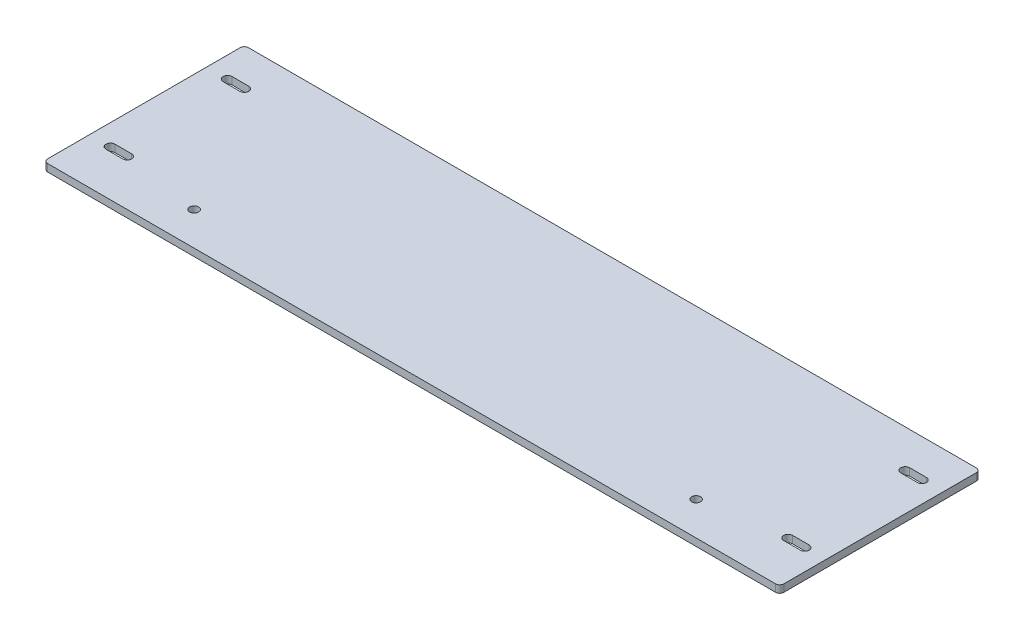
SolidWorks part; units mm, degrees
material "PC High Viscosity"
ref_plane "Front" through (0, 0, 0) normal (0, 0, 1) x (1, 0, 0)
ref_plane "Top" through (0, 0, 0) normal (0, 1, 0) x (1, 0, 0)
ref_plane "Right" through (0, 0, 0) normal (1, 0, 0) x (0, 0, -1)
sketch "Sketch1" plane through (0, 0, 0) normal (0, 1, 0) x (1, 0, 0)
  line L0 (15.875, 34.925) -> (28.575, 34.925) construction
  line L1 (0, 0) -> (558.8, 0)
  line L2 (0, 0) -> (0, 152.4)
  line L3 (0, 152.4) -> (558.8, 152.4)
  line L4 (558.8, 0) -> (558.8, 152.4)
  line L5 (15.875, 38.3032) -> (28.575, 38.3032)
  line L6 (15.875, 31.5468) -> (28.575, 31.5468)
  line L7 (22.225, 34.925) -> (22.225, 123.825) construction
  line L8 (15.875, 123.825) -> (28.575, 123.825) construction
  line L9 (15.875, 127.2032) -> (28.575, 127.2032)
  line L10 (15.875, 120.4468) -> (28.575, 120.4468)
  line L11 (22.225, 123.825) -> (66.675, 123.825) construction
  line L12 (66.675, 123.825) -> (66.675, 34.925) construction
  line L13 (66.675, 34.925) -> (22.225, 34.925) construction
  line L14 (60.325, 123.825) -> (73.025, 123.825) construction
  line L15 (60.325, 127.2032) -> (73.025, 127.2032) construction
  line L16 (60.325, 120.4468) -> (73.025, 120.4468) construction
  line L17 (60.325, 34.925) -> (73.025, 34.925) construction
  line L18 (60.325, 38.3032) -> (73.025, 38.3032) construction
  line L19 (60.325, 31.5468) -> (73.025, 31.5468) construction
  line L20 (536.575, 123.825) -> (536.575, 34.925) construction
  line L21 (542.925, 123.825) -> (530.225, 123.825) construction
  line L22 (542.925, 120.4468) -> (530.225, 120.4468)
  line L23 (542.925, 127.2032) -> (530.225, 127.2032)
  line L24 (542.925, 34.925) -> (530.225, 34.925) construction
  line L25 (542.925, 31.5468) -> (530.225, 31.5468)
  line L26 (542.925, 38.3032) -> (530.225, 38.3032)
  arc A0 (15.875, 38.3032) -> (15.875, 31.5468) centre (15.875, 34.925) ccw
  arc A1 (28.575, 31.5468) -> (28.575, 38.3032) centre (28.575, 34.925) ccw
  arc A2 (15.875, 127.2032) -> (15.875, 120.4468) centre (15.875, 123.825) ccw
  arc A3 (28.575, 120.4468) -> (28.575, 127.2032) centre (28.575, 123.825) ccw
  arc A4 (60.325, 127.2032) -> (60.325, 120.4468) centre (60.325, 123.825) ccw construction
  arc A5 (73.025, 120.4468) -> (73.025, 127.2032) centre (73.025, 123.825) ccw construction
  arc A6 (60.325, 38.3032) -> (60.325, 31.5468) centre (60.325, 34.925) ccw construction
  arc A7 (73.025, 31.5468) -> (73.025, 38.3032) centre (73.025, 34.925) ccw construction
  arc A8 (542.925, 120.4468) -> (542.925, 127.2032) centre (542.925, 123.825) ccw
  arc A9 (530.225, 127.2032) -> (530.225, 120.4468) centre (530.225, 123.825) ccw
  arc A10 (542.925, 31.5468) -> (542.925, 38.3032) centre (542.925, 34.925) ccw
  arc A11 (530.225, 38.3032) -> (530.225, 31.5468) centre (530.225, 34.925) ccw
  point P7 (22.225, 34.925)
  point P13 (22.225, 123.825)
  point P25 (66.675, 123.825)
  point P31 (66.675, 34.925)
  point P40 (536.575, 123.825)
  point P47 (536.575, 34.925)
  dimension "D1" = 6.7564
  dimension "D2" = 34.925
  dimension "D3" = 12.7
  dimension "D4" = 22.225
  dimension "D5" = 152.4
  dimension "D6" = 28.575
  dimension "D7" = 44.45
  dimension "D8" = 22.225
  dimension "D9" = 514.35
extrude "Boss-Extrude1" add sketch "Sketch1" along normal blind 5.588
fillet "Fillet1" radius 3.175 4 edges at (0, 2.794, -152.4) (558.8, 2.794, -152.4) (0, 2.794, 0) (558.8, 2.794, 0)
sketch "Sketch2" plane through (0, 5.588, 0) normal (0, 1, 0) x (1, 0, 0)
  line L0 (279.4, 152.4) -> (279.4, 0) construction
  line L1 (555.625, 152.4) -> (3.175, 152.4) construction
  line L2 (3.175, 0) -> (555.625, 0) construction
  line L4 (469.9, 25.4) -> (88.9, 25.4) construction
  line L5 (469.9, 25.4) -> (469.9, 127) construction
  line L6 (469.9, 127) -> (88.9, 127) construction
  line L7 (88.9, 25.4) -> (88.9, 127) construction
  line L8 (469.9, 25.4) -> (88.9, 127) construction
  line L9 (469.9, 127) -> (88.9, 25.4) construction
  circle A1 centre (88.9, 25.4) radius 3.3782
  circle A2 centre (469.9, 25.4) radius 3.3782
  point P6 (279.4, 76.2)
  dimension "D3" = 6.7564
  dimension "D1" = 25.4
  dimension "D2" = 381
extrude "Cut-Extrude1" cut sketch "Sketch2" against normal through all
